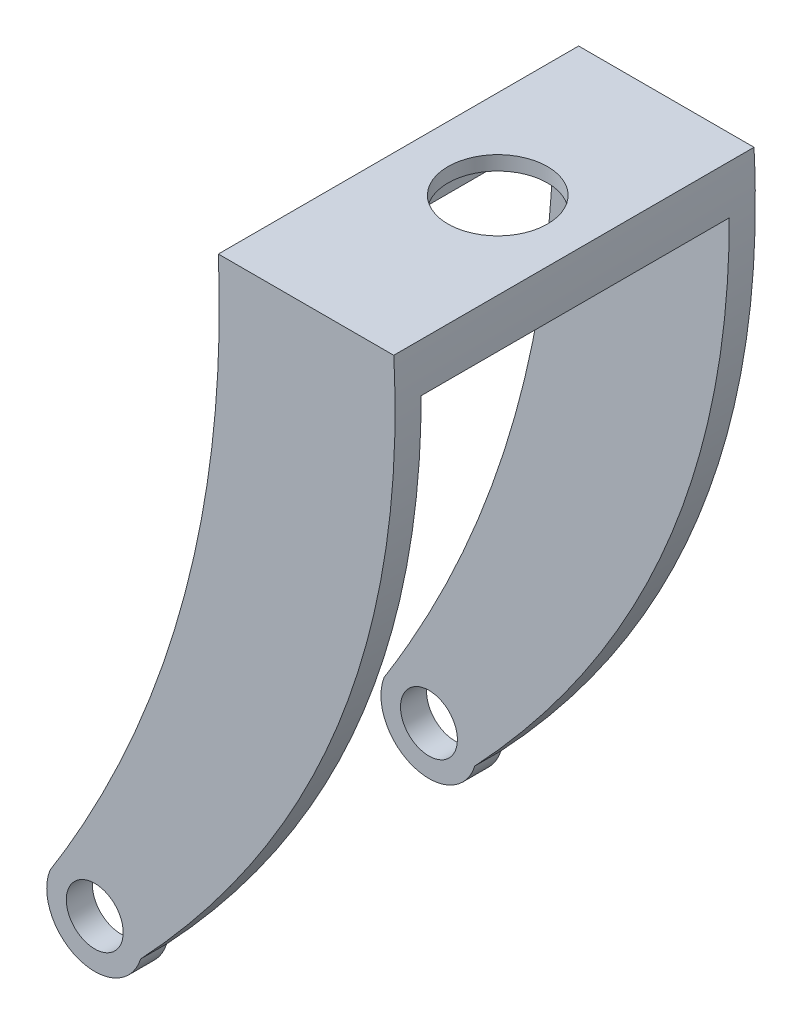
SolidWorks part; units mm, degrees
material "AISI 1020"
ref_plane "Alzado" through (0, 0, 0) normal (0, 0, 1) x (1, 0, 0)
ref_plane "Planta" through (0, 0, 0) normal (0, 1, 0) x (1, 0, 0)
ref_plane "Vista lateral" through (0, 0, 0) normal (1, 0, 0) x (0, 0, -1)
sketch "Croquis1" plane through (0, 0, 0) normal (0, 0, 1) x (1, 0, 0)
  line L1 (40.6236, 29.9854) -> (37.5489, -109.6871) construction
  line L2 (-22.4511, -114.1396) -> (37.5489, -114.1396) construction
  line L3 (37.5489, -114.1396) -> (37.5489, -109.6871) construction
  line L4 (3.6236, 29.9854) -> (40.6236, 29.9854)
  arc A0 (-31.8824, -100.3312) -> (-12.776, -106.999) centre (-22.4511, -104.0146) ccw
  circle A1 centre (-22.4511, -104.0146) radius 6
  spline S0 degree 2 poles (40.6236, 29.9854) (44.758, -45.9341) (-12.776, -106.999) knots 0 0 0 1 1 1
  spline S1 degree 2 poles (3.6236, 29.9854) (6.5104, -38.8087) (-31.8824, -100.3312) knots 0 0 0 1 1 1
  dimension "D4" = 20.25
  dimension "D2" = 12
  dimension "D1" = 37
  dimension "D5" = 60
extrude "Saliente-Extruir1" add sketch "Croquis1" along normal blind 76
sketch "Croquis2" plane through (0, 0, 0) normal (1, 0, 0) x (0, 0, -1)
  line L0 (-70.5, -114.1396) -> (-70.5, 19.9854)
  line L1 (-76, -114.1396) -> (0, -114.1396) construction
  line L2 (-70.5, 19.9854) -> (-5.5, 19.9854)
  line L3 (-5.5, 19.9854) -> (-5.5, -114.1396)
  line L4 (-5.5, -114.1396) -> (-70.5, -114.1396)
  line L5 (0, -114.1396) -> (0, -100.3312) construction
  line L6 (-76, -100.3312) -> (-76, -114.1396) construction
  line L8 (-76, 29.9854) -> (0, 29.9854) construction
  dimension "D1" = 65
  dimension "D2" = 10
  dimension "D3" = 5.5
  dimension "D4" = 5.5
extrude "Cortar-Extruir1" cut sketch "Croquis2" along normal blind 53 and the other way blind 83
sketch "Croquis5" plane through (0, 19.9854, 0) normal (0, -1, 0) x (1, 0, 0)
  line L0 (40.9007, 70.5) -> (40.9007, 5.5) construction
  line L1 (10.8251, 63.739) -> (33.9007, 63.739)
  line L2 (6.8251, 59.739) -> (6.8251, 11.8604)
  line L3 (10.8251, 7.8604) -> (33.9007, 7.8604)
  line L4 (37.9007, 59.739) -> (37.9007, 11.8604)
  line L5 (3.8251, 5.5) -> (3.8251, 70.5) construction
  arc A0 (37.9007, 11.8604) -> (33.9007, 7.8604) centre (33.9007, 11.8604) cw
  arc A1 (10.8251, 7.8604) -> (6.8251, 11.8604) centre (10.8251, 11.8604) cw
  arc A2 (33.9007, 63.739) -> (37.9007, 59.739) centre (33.9007, 59.739) cw
  arc A3 (6.8251, 59.739) -> (10.8251, 63.739) centre (10.8251, 59.739) cw
  dimension "D3" = 4
  dimension "D1" = 3
  dimension "D2" = 3
extrude "Cortar-Extruir4" cut sketch "Croquis5" against normal blind 7
sketch "Croquis6" plane through (0, 26.9854, 0) normal (0, -1, 0) x (-1, 0, 0)
  circle A0 centre (-22.3629, -35.7997) radius 10.5
  dimension "D1" = 21
extrude "Cortar-Extruir5" cut sketch "Croquis6" against normal blind 7
